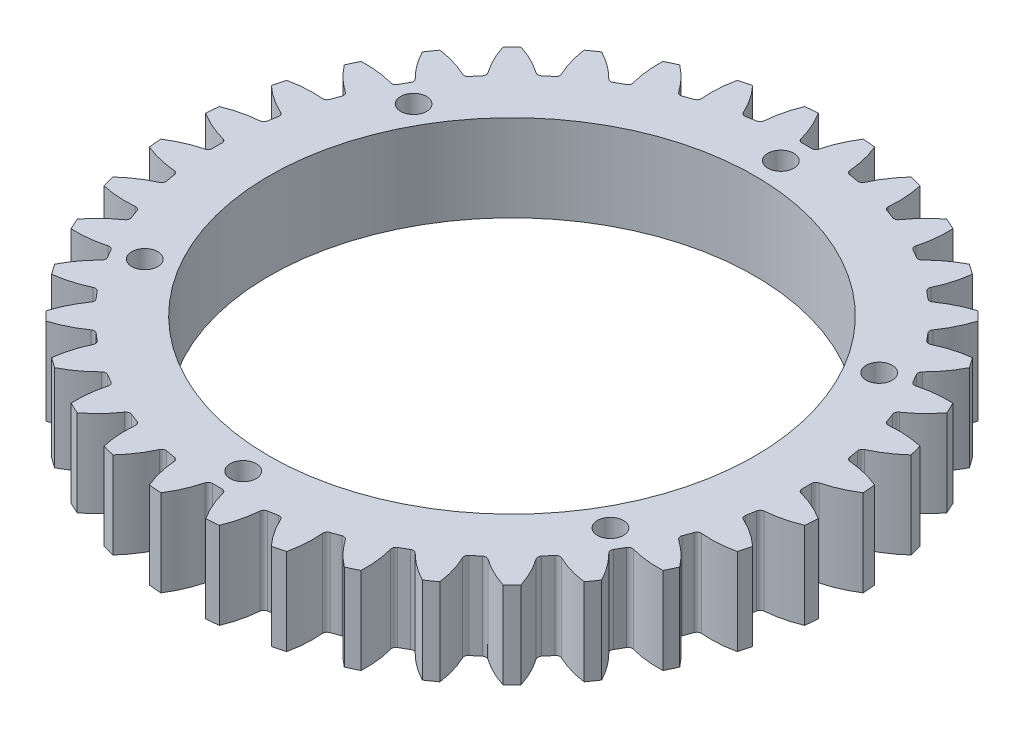
SolidWorks part; units mm, degrees
ref_plane "前视基准面" through (0, 0, 0) normal (0, 0, 1) x (1, 0, 0)
ref_plane "上视基准面" through (0, 0, 0) normal (0, 1, 0) x (1, 0, 0)
ref_plane "右视基准面" through (0, 0, 0) normal (1, 0, 0) x (0, 0, -1)
other "Configuration Table"
sketch "草图1" plane through (0, 0, 0) normal (0, 1, 0) x (1, 0, 0)
  line L0 (0, 47.2508) -> (0, -53.1693) construction
  circle A0 centre (0, 0) radius 28
  circle A1 centre (0, 0) radius 38
  circle A2 centre (0, 0) radius 34 construction
  circle A3 centre (0, 0) radius 31 construction
  circle A4 centre (0, 31) radius 1.5
  circle A5 centre (26.8468, 15.5) radius 1.5
  circle A6 centre (26.8468, -15.5) radius 1.5
  circle A7 centre (0, -31) radius 1.5
  circle A8 centre (-26.8468, -15.5) radius 1.5
  circle A9 centre (-26.8468, 15.5) radius 1.5
  point P23 (0, 0)
  dimension "D1" = 56
  dimension "D2" = 76
  dimension "D3" = 68
  dimension "D4" = 62
  dimension "D5" = 3
  dimension "D6" = 6
extrude "凸台-拉伸1" add sketch "草图1" along normal blind 10
sketch "草图2" plane through (0, 0, 0) normal (0, 1, 0) x (1, 0, 0)
  line L0 (0, -46.0485) -> (0, 53.1455) construction
  line L1 (0, 0) -> (2.3204, 53.1454) construction
  line L2 (1.5703, 35.9657) -> (53.5834, 33.6948) construction
  line L3 (1.5703, 35.9657) -> (42.3444, 19.0765) construction
  line L4 (0, 0) -> (12.9458, 31.2539) construction
  circle A0 centre (0, 0) radius 38 construction
  circle A1 centre (0, 0) radius 38 construction
  circle A2 centre (0, 0) radius 36 construction
  arc A3 (2.5884, 37.9117) -> (-2.5884, 37.9117) centre (0, 0) ccw
  arc A4 (2.5884, 37.9117) -> (1.0337, 34.3691) centre (12.9458, 31.2539) ccw
  arc A5 (0.542, 33.9957) -> (-0.542, 33.9957) centre (0, 0) ccw
  arc A6 (1.0337, 34.3691) -> (0.542, 33.9957) centre (0.5499, 34.4956) cw
  arc A7 (-1.0337, 34.3691) -> (-0.542, 33.9957) centre (-0.5499, 34.4956) ccw
  arc A8 (-2.5884, 37.9117) -> (-1.0337, 34.3691) centre (-12.9458, 31.2539) cw
  point P17 (1.5703, 35.9657)
  dimension "D2" = 72
  dimension "D3" = 20
  dimension "D4" = 34
  dimension "D5" = 0.5
  dimension "D1" = 2.5
extrude "切除-拉伸1" cut sketch "草图2" along normal through all
pattern_circular "阵列(圆周)1" count 36 over 360 about axis through (0, 0, 0) along (0, 1, 0) of "切除-拉伸1"
sketch "草图3" plane through (0, 0, 0) normal (0, 1, 0) x (1, 0, 0)
  circle A0 centre (0, 0) radius 36 construction
  dimension "D1" = 72
